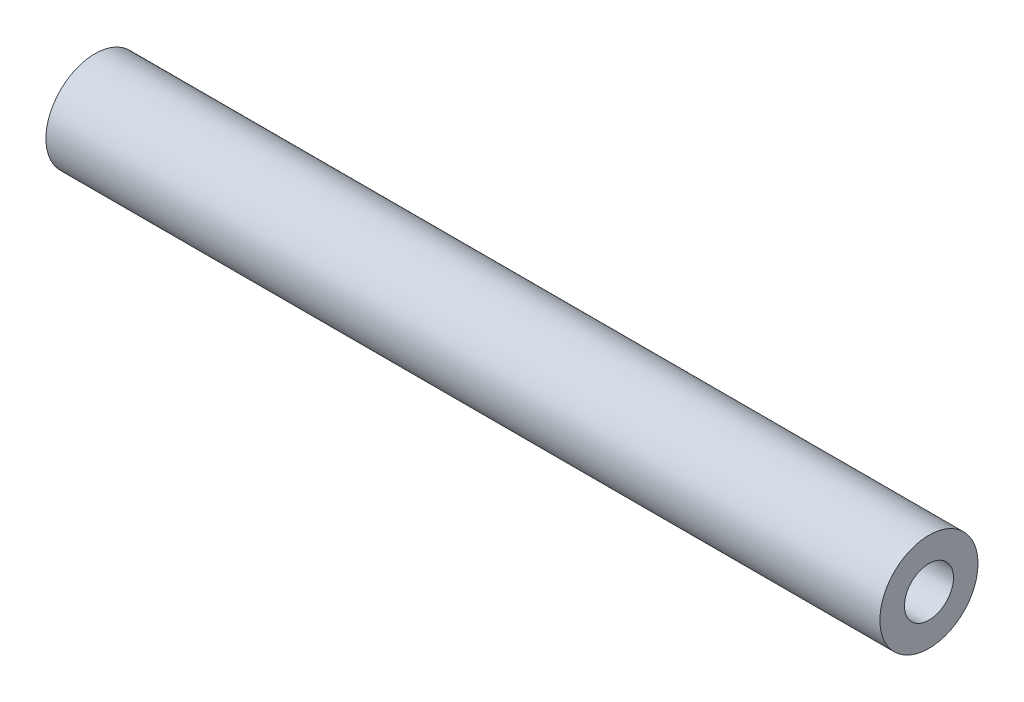
SolidWorks part; units mm, degrees
material "moto_orange"
ref_plane "Front Plane" through (0, 0, 0) normal (0, 0, 1) x (1, 0, 0)
ref_plane "Top Plane" through (0, 0, 0) normal (0, 1, 0) x (1, 0, 0)
ref_plane "Right Plane" through (0, 0, 0) normal (1, 0, 0) x (0, 0, -1)
sketch "Sketch2" plane through (0, 0, 0) normal (1, 0, 0) x (0, 0, -1)
  circle A0 centre (0, 0) radius 5
  circle A1 centre (0, 0) radius 2.5
  dimension "D1" = 10
  dimension "D2" = 5
extrude "Boss-Extrude1" add sketch "Sketch2" along normal blind 85
